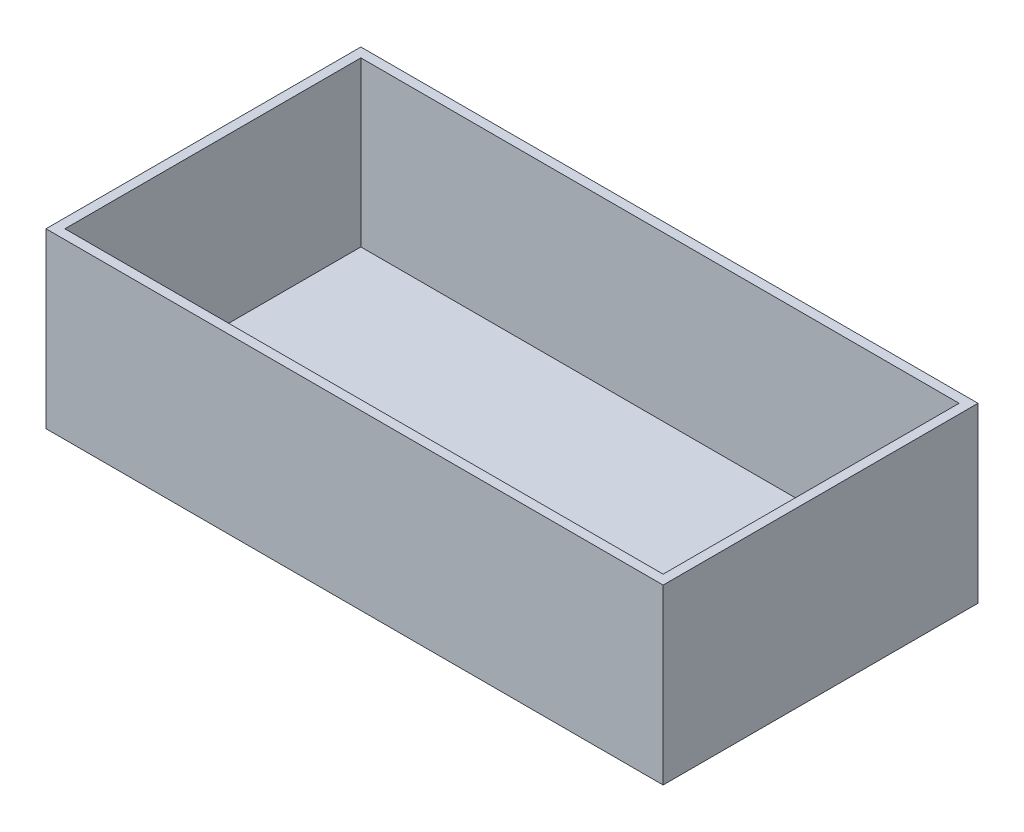
SolidWorks part; units mm, degrees
ref_plane "Front Plane" through (0, 0, 0) normal (0, 0, 1) x (1, 0, 0)
ref_plane "Top Plane" through (0, 0, 0) normal (0, 1, 0) x (1, 0, 0)
ref_plane "Right Plane" through (0, 0, 0) normal (1, 0, 0) x (0, 0, -1)
sketch "Sketch1" plane through (0, 0, 0) normal (0, 1, 0) x (1, 0, 0)
  line L1 (-98, -50) -> (98, -50)
  line L2 (-98, -50) -> (-98, 50)
  line L3 (-98, 50) -> (98, 50)
  line L4 (98, -50) -> (98, 50)
  line L5 (-98, -50) -> (98, 50) construction
  line L6 (-98, 50) -> (98, -50) construction
  point P0 (0, 0)
  dimension "D1" = 196
  dimension "D2" = 100
extrude "Boss-Extrude1" add sketch "Sketch1" along normal blind 55
sketch "Sketch2" plane through (0, 55, 0) normal (0, 1, 0) x (1, 0, 0)
  line L0 (98, -50) -> (98, 50) construction
  line L1 (-95, -47) -> (95, -47)
  line L2 (-95, -47) -> (-95, 47)
  line L3 (-95, 47) -> (95, 47)
  line L4 (95, -47) -> (95, 47)
  line L5 (-95, -47) -> (95, 47) construction
  line L6 (-95, 47) -> (95, -47) construction
  line L7 (-98, -50) -> (98, -50) construction
  point P0 (0, 0)
  dimension "D1" = 3
  dimension "D2" = 3
extrude "Cut-Extrude1" cut sketch "Sketch2" against normal blind 52
